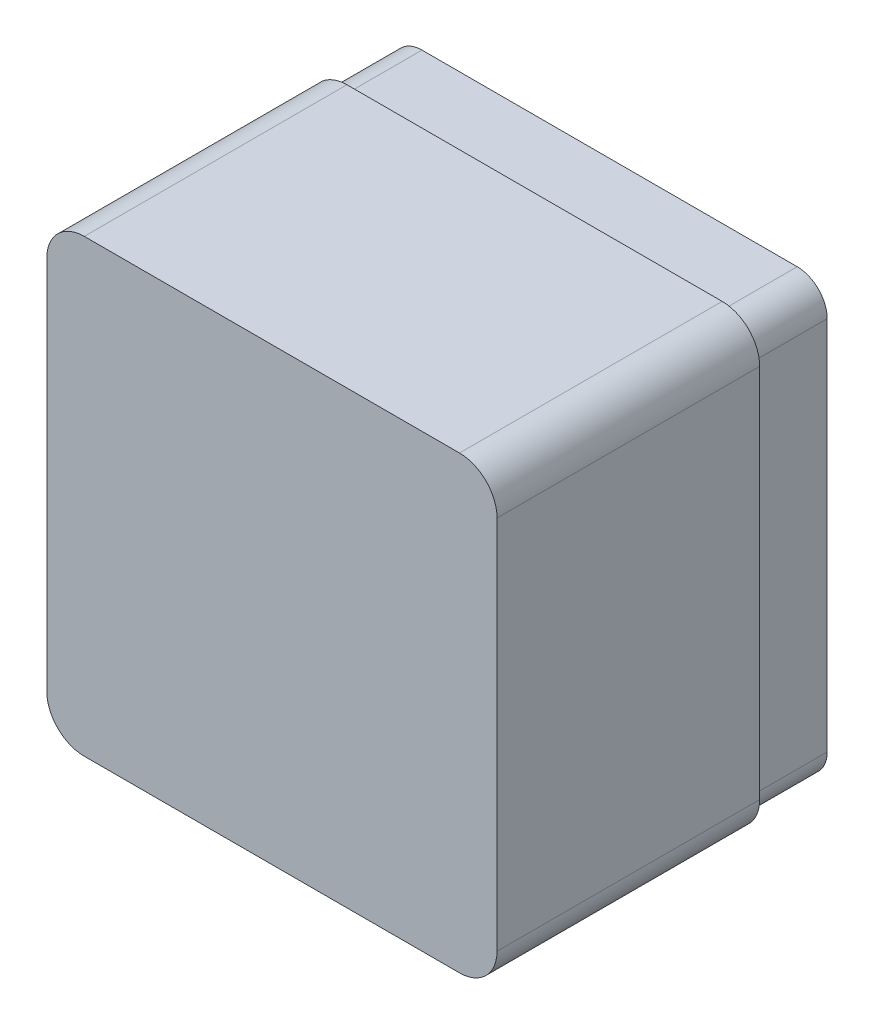
SolidWorks part; units mm, degrees
ref_plane "Front Plane" through (0, 0, 0) normal (0, 0, 1) x (1, 0, 0)
ref_plane "Top Plane" through (0, 0, 0) normal (0, 1, 0) x (1, 0, 0)
ref_plane "Right Plane" through (0, 0, 0) normal (1, 0, 0) x (0, 0, -1)
sketch "Sketch1" plane through (0, 0, 0) normal (0, 0, 1) x (1, 0, 0)
  line L0 (0, 60) -> (0, -60) construction
  line L5 (-60, 60) -> (60, 60)
  line L6 (-60, 60) -> (-60, -60)
  line L7 (-60, -60) -> (60, -60)
  line L8 (60, 60) -> (60, -60)
  line L10 (-60, 0) -> (60, 0) construction
  dimension "D1" = 120
  dimension "D2" = 120
extrude "Boss-Extrude1" add sketch "Sketch1" along normal blind 90
fillet "Fillet1" radius 10 4 edges at (-60, -60, 45) (60, -60, 45) (60, 60, 45) (-60, 60, 45)
shell "Shell1" thickness 4
sketch "Sketch3" plane through (0, 0, 0) normal (0, 0, -1) x (-1, 0, 0)
  line L0 (50, 58) -> (-50, 58)
  line L1 (-58, 50) -> (-58, -50)
  line L2 (-50, -58) -> (50, -58)
  line L3 (58, -50) -> (58, 50)
  line L4 (-50, -60) -> (50, -60)
  line L5 (60, -50) -> (60, 50)
  line L6 (50, 60) -> (-50, 60)
  line L7 (-60, 50) -> (-60, -50)
  line L8 (-50, -60) -> (50, -60)
  line L9 (60, -50) -> (60, 50)
  line L10 (50, 60) -> (-50, 60)
  line L11 (-60, 50) -> (-60, -50)
  arc A0 (58, 50) -> (50, 58) centre (50, 50) ccw
  arc A1 (-50, 58) -> (-58, 50) centre (-50, 50) ccw
  arc A2 (-58, -50) -> (-50, -58) centre (-50, -50) ccw
  arc A3 (50, -58) -> (58, -50) centre (50, -50) ccw
  arc A4 (50, -60) -> (60, -50) centre (50, -50) ccw
  arc A5 (60, 50) -> (50, 60) centre (50, 50) ccw
  arc A6 (-50, 60) -> (-60, 50) centre (-50, 50) ccw
  arc A7 (-60, -50) -> (-50, -60) centre (-50, -50) ccw
  arc A8 (50, -60) -> (60, -50) centre (50, -50) ccw
  arc A9 (60, 50) -> (50, 60) centre (50, 50) ccw
  arc A10 (-50, 60) -> (-60, 50) centre (-50, 50) ccw
  arc A11 (-60, -50) -> (-50, -60) centre (-50, -50) ccw
  dimension "D1" = 0
  dimension "D2" = 2
extrude "Cut-Extrude1" cut sketch "Sketch3" against normal blind 20
